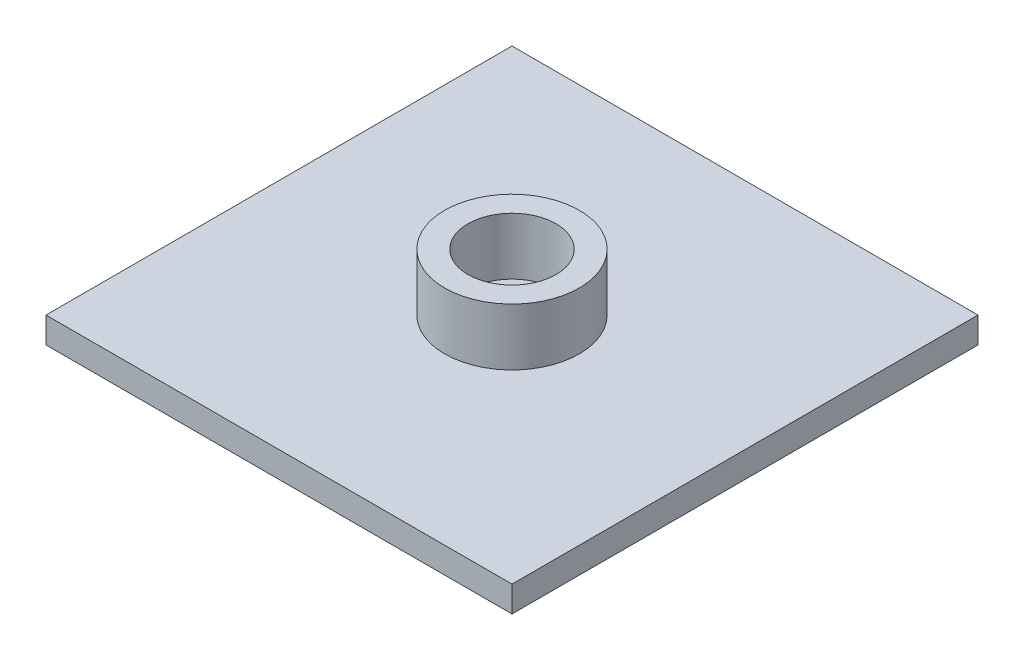
SolidWorks part; units mm, degrees
ref_plane "Front Plane" through (0, 0, 0) normal (0, 0, 1) x (1, 0, 0)
ref_plane "Top Plane" through (0, 0, 0) normal (0, 1, 0) x (1, 0, 0)
ref_plane "Right Plane" through (0, 0, 0) normal (1, 0, 0) x (0, 0, -1)
sketch "Sketch1" plane through (0, 0, 0) normal (0, 1, 0) x (1, 0, 0)
  line L1 (0, 0) -> (114.3, 0)
  line L2 (0, 0) -> (0, 114.3)
  line L3 (0, 114.3) -> (114.3, 114.3)
  line L4 (114.3, 0) -> (114.3, 114.3)
  dimension "D1" = 114.3
  dimension "114.3" = 114.3
extrude "Boss-Extrude1" add sketch "Sketch1" along normal blind 6.35
sketch "Sketch2" plane through (0, 6.35, 0) normal (0, 1, 0) x (1, 0, 0)
  line L0 (0, 57.15) -> (114.3, 57.15) construction
  line L1 (0, 114.3) -> (0, 0) construction
  line L2 (114.3, 0) -> (114.3, 114.3) construction
  circle A0 centre (57.15, 57.15) radius 10.16
  circle A1 centre (57.15, 57.15) radius 16.51
  dimension "D1" = 20.32
  dimension "D2" = 33.02
extrude "Boss-Extrude2" add sketch "Sketch2" along normal blind 14 contours A1
sketch "Sketch3" plane through (0, 20.35, 0) normal (0, 1, 0) x (1, 0, 0)
  line L0 (40.64, 57.15) -> (73.66, 57.15) construction
  circle A0 centre (57.15, 57.15) radius 16.51 construction
  circle A1 centre (57.15, 57.15) radius 16.51 construction
  circle A2 centre (57.15, 57.15) radius 10.8
  dimension "D1" = 21.6
extrude "Cut-Extrude1" cut sketch "Sketch3" against normal blind 14
